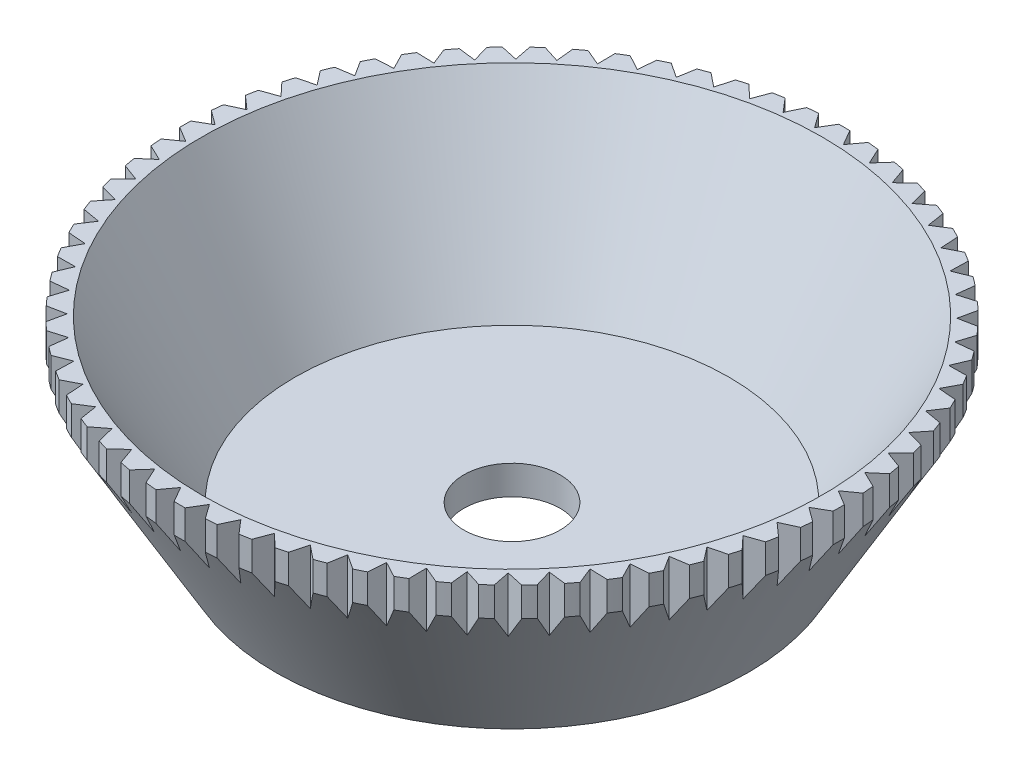
SolidWorks part; units mm, degrees
ref_plane "Front Plane" through (0, 0, 0) normal (0, 0, 1) x (1, 0, 0)
ref_plane "Top Plane" through (0, 0, 0) normal (0, 1, 0) x (1, 0, 0)
ref_plane "Right Plane" through (0, 0, 0) normal (1, 0, 0) x (0, 0, -1)
sketch "Sketch1" plane through (0, 0, 0) normal (0, 0, 1) x (1, 0, 0)
  line L1 (12.1935, 5.1749) -> (17, 13.5)
  line L2 (11.1935, 6.6749) -> (16, 15)
  line L4 (0, 5.1749) -> (12.1935, 5.1749) construction
  line L5 (0, 5.1749) -> (0, 15) construction
  line L6 (12.1935, 5.1749) -> (2.4775, 5.1749)
  line L7 (2.4775, 5.1749) -> (2.4775, 6.6749)
  line L8 (2.4775, 6.6749) -> (11.1935, 6.6749)
  line L9 (17, 13.5) -> (17, 15)
  line L10 (17, 15) -> (16, 15)
  point P3 (0.0454, 15.8146)
  point P9 (0.085, 15)
  point P11 (0, 5.1749)
  dimension "D1" = 17
  dimension "D2" = 120
  dimension "D3" = 15
  dimension "D4" = 1
  dimension "D5" = 1.5
  dimension "D6" = 1.5
revolve "Revolve1" add sketch "Sketch1" angle 360 about L5
sketch "Sketch2" plane through (0, 15, 0) normal (0, 1, 0) x (1, 0, 0)
  line L0 (0.1396, -16.9994) -> (0.6108, -16.2166)
  line L1 (0.6108, -16.2166) -> (1.1396, -16.9618)
  arc A0 (0.1396, -16.9994) -> (1.1396, -16.9618) centre (0, 0) ccw
  circle A1 centre (0, 0) radius 17 construction
  point P6 (0.8638, -17.0367)
  point P7 (0.9781, -17.7869)
  point P9 (1.1479, -17.8024)
  dimension "D1" = 1
extrude "Cut-Extrude1" cut sketch "Sketch2" against normal blind 10
pattern_circular "CirPattern1" count 68 over 360 about axis through (0, 0, 0) along (0, 1, 0) of "Cut-Extrude1"
